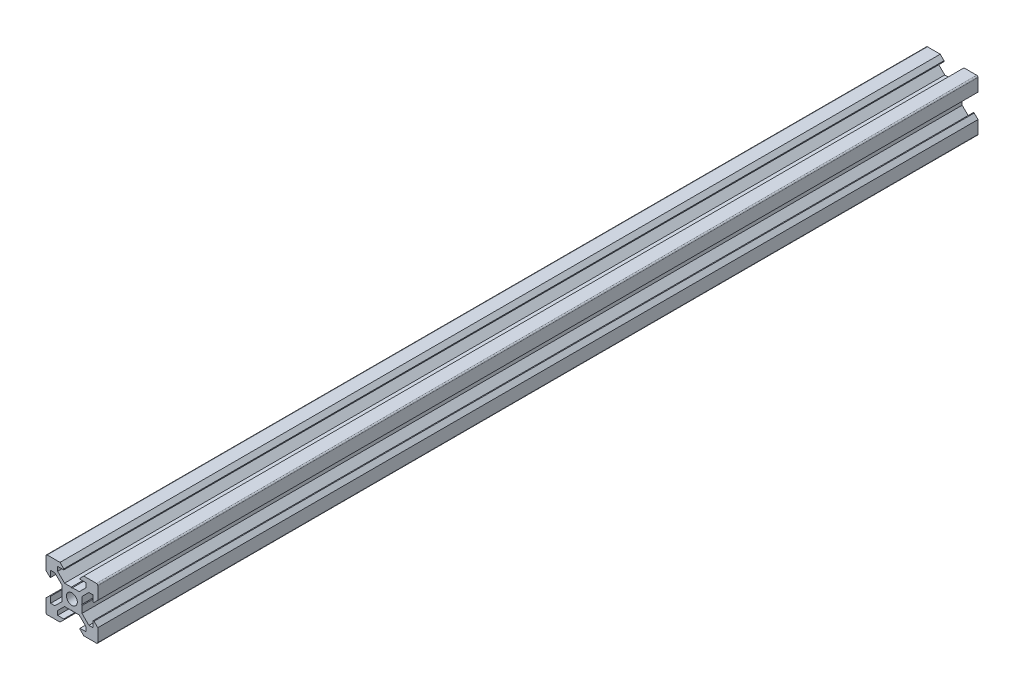
SolidWorks part; units mm, degrees
material "6061-T6 (SS)"
ref_plane "Front Plane" through (0, 0, 0) normal (0, 0, 1) x (1, 0, 0)
ref_plane "Top Plane" through (0, 0, 0) normal (0, 1, 0) x (1, 0, 0)
ref_plane "Right Plane" through (0, 0, 0) normal (1, 0, 0) x (0, 0, -1)
sketch "Sketch1" plane through (0, 0, 0) normal (0, 0, 1) x (1, 0, 0)
  line L1 (9.5, -10) -> (-9.5, -10)
  line L2 (10, -9.5) -> (10, 9.5)
  line L3 (9.5, 10) -> (-9.5, 10)
  line L4 (-10, -9.5) -> (-10, 9.5)
  line L5 (10, -10) -> (-10, 10) construction
  line L6 (10, 10) -> (-10, -10) construction
  circle A0 centre (0, 0) radius 2.1
  arc A1 (-9.5, 10) -> (-10, 9.5) centre (-9.5, 9.5) ccw
  arc A2 (10, 9.5) -> (9.5, 10) centre (9.5, 9.5) ccw
  arc A3 (9.5, -10) -> (10, -9.5) centre (9.5, -9.5) ccw
  arc A4 (-9.5, -10) -> (-10, -9.5) centre (-9.5, -9.5) cw
  point P0 (0, 0)
  line B0 (0, 0) -> (0, 10) construction
  line B1 (0, 3.69) -> (-0.21, 3.9)
  line B2 (-0.21, 3.9) -> (-2.8393, 3.9)
  line B3 (-2.8393, 3.9) -> (-5.5, 6.5607)
  line B4 (-5.5, 6.5607) -> (-5.5, 8.2)
  line B5 (-5.5, 8.2) -> (-3.125, 8.2)
  line B6 (-3.125, 8.2) -> (-3.125, 8.545)
  line B7 (-3.125, 8.545) -> (-4.58, 10)
  line B8 (-4.58, 10) -> (4.58, 10)
  line B9 (0, 0) -> (-5.9132, 5.9132) construction
  line B10 (3.125, 8.545) -> (4.58, 10)
  line B11 (3.125, 8.2) -> (3.125, 8.545)
  line B12 (5.5, 8.2) -> (3.125, 8.2)
  line B13 (5.5, 6.5607) -> (5.5, 8.2)
  line B14 (2.8393, 3.9) -> (5.5, 6.5607)
  line B15 (0.21, 3.9) -> (2.8393, 3.9)
  line B16 (0, 3.69) -> (0.21, 3.9)
  line B17 (0, 0) -> (-10, 0) construction
  line B18 (-3.69, 0) -> (-3.9, -0.21)
  line B19 (-3.9, -0.21) -> (-3.9, -2.8393)
  line B20 (-3.9, -2.8393) -> (-6.5607, -5.5)
  line B21 (-6.5607, -5.5) -> (-8.2, -5.5)
  line B22 (-8.2, -5.5) -> (-8.2, -3.125)
  line B23 (-8.2, -3.125) -> (-8.545, -3.125)
  line B24 (-8.545, -3.125) -> (-10, -4.58)
  line B25 (-10, -4.58) -> (-10, 4.58)
  line B26 (0, 0) -> (-5.9132, -5.9132) construction
  line B27 (-8.545, 3.125) -> (-10, 4.58)
  line B28 (-8.2, 3.125) -> (-8.545, 3.125)
  line B29 (-8.2, 5.5) -> (-8.2, 3.125)
  line B30 (-6.5607, 5.5) -> (-8.2, 5.5)
  line B31 (-3.9, 2.8393) -> (-6.5607, 5.5)
  line B32 (-3.9, 0.21) -> (-3.9, 2.8393)
  line B33 (-3.69, 0) -> (-3.9, 0.21)
  line B34 (0, 0) -> (0, -10) construction
  line B35 (0, -3.69) -> (0.21, -3.9)
  line B36 (0.21, -3.9) -> (2.8393, -3.9)
  line B37 (2.8393, -3.9) -> (5.5, -6.5607)
  line B38 (5.5, -6.5607) -> (5.5, -8.2)
  line B39 (5.5, -8.2) -> (3.125, -8.2)
  line B40 (3.125, -8.2) -> (3.125, -8.545)
  line B41 (3.125, -8.545) -> (4.58, -10)
  line B42 (4.58, -10) -> (-4.58, -10)
  line B43 (0, 0) -> (5.9132, -5.9132) construction
  line B44 (-3.125, -8.545) -> (-4.58, -10)
  line B45 (-3.125, -8.2) -> (-3.125, -8.545)
  line B46 (-5.5, -8.2) -> (-3.125, -8.2)
  line B47 (-5.5, -6.5607) -> (-5.5, -8.2)
  line B48 (-2.8393, -3.9) -> (-5.5, -6.5607)
  line B49 (-0.21, -3.9) -> (-2.8393, -3.9)
  line B50 (0, -3.69) -> (-0.21, -3.9)
  line B51 (0, 0) -> (10, 0) construction
  line B52 (3.69, 0) -> (3.9, 0.21)
  line B53 (3.9, 0.21) -> (3.9, 2.8393)
  line B54 (3.9, 2.8393) -> (6.5607, 5.5)
  line B55 (6.5607, 5.5) -> (8.2, 5.5)
  line B56 (8.2, 5.5) -> (8.2, 3.125)
  line B57 (8.2, 3.125) -> (8.545, 3.125)
  line B58 (8.545, 3.125) -> (10, 4.58)
  line B59 (10, 4.58) -> (10, -4.58)
  line B60 (0, 0) -> (5.9132, 5.9132) construction
  line B61 (8.545, -3.125) -> (10, -4.58)
  line B62 (8.2, -3.125) -> (8.545, -3.125)
  line B63 (8.2, -5.5) -> (8.2, -3.125)
  line B64 (6.5607, -5.5) -> (8.2, -5.5)
  line B65 (3.9, -2.8393) -> (6.5607, -5.5)
  line B66 (3.9, -0.21) -> (3.9, -2.8393)
  line B67 (3.69, 0) -> (3.9, -0.21)
sketch_block_instance "V Slot 1-4"
sketch_block "V Slot 1" parameters "D1"=10, "D2"=11, "D3"=4.3, "D4"=1.8, "D5"=0.21, "D6"=45, "D7"=9.16, "D8"=1.5, "D9"=6.25
sketch_block_instance "V Slot 1-5"
sketch_block_instance "V Slot 1-6"
sketch_block_instance "V Slot 1-7" parameters "D1"=31.2546, "D3"=0.5, "D2"=9.6469
extrude "Boss-Extrude1" add sketch "Sketch1" along normal blind 340 contours B67 B52 B53 B54 B55 B56 B57 B58 L2 A2 L3 B10 B11 B12 B13 B14 B15 B16 B1 B2 B3 B4 B5 B6 B7 A1 L4 B27 B28 B29 B30 B31 B32 B33 B18 B19 B20 B21 B22 B23 B24 A4 L1 B44 B45 B46 B47 B48 B49
